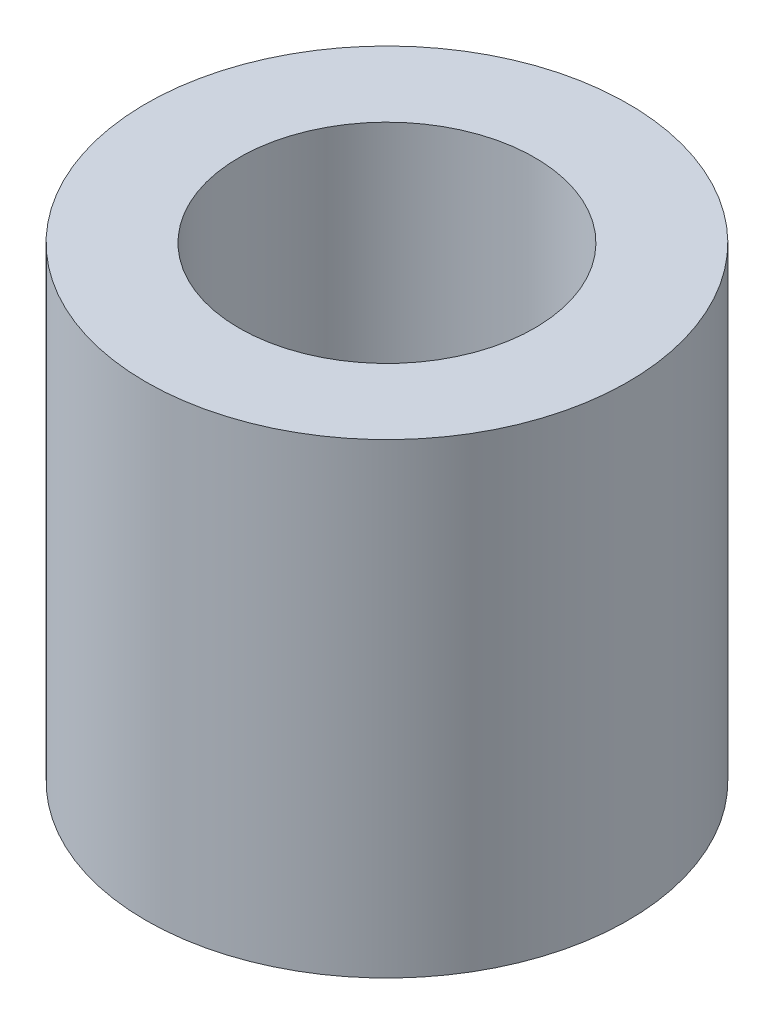
SolidWorks part; units mm, degrees
ref_plane "Front Plane" through (0, 0, 0) normal (0, 0, 1) x (1, 0, 0)
ref_plane "Top Plane" through (0, 0, 0) normal (0, 1, 0) x (1, 0, 0)
ref_plane "Right Plane" through (0, 0, 0) normal (1, 0, 0) x (0, 0, -1)
sketch "Sketch1" plane through (0, 0, 0) normal (0, 1, 0) x (1, 0, 0)
  circle A0 centre (0, 0) radius 4.025
  circle A1 centre (0, 0) radius 6.565
  dimension "D1" = 8.05
  dimension "D2" = 2.54
extrude "Boss-Extrude1" add sketch "Sketch1" along normal blind 12.7
